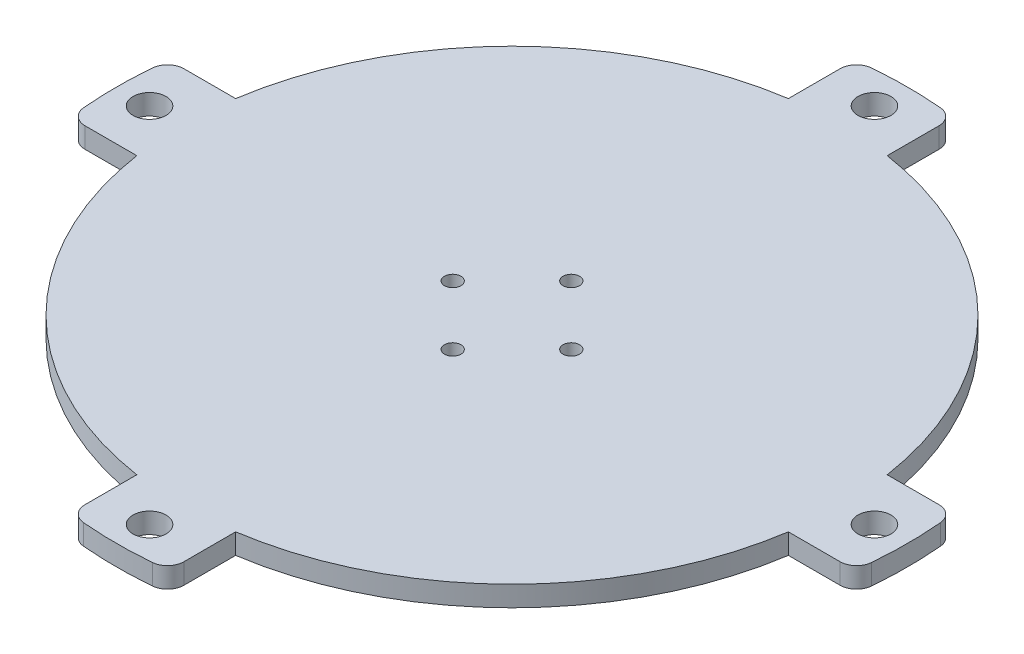
SolidWorks part; units mm, degrees
ref_plane "Front Plane" through (0, 0, 0) normal (0, 0, 1) x (1, 0, 0)
ref_plane "Top Plane" through (0, 0, 0) normal (0, 1, 0) x (1, 0, 0)
ref_plane "Right Plane" through (0, 0, 0) normal (1, 0, 0) x (0, 0, -1)
sketch "Sketch1" plane through (0, 0, 0) normal (0, 1, 0) x (1, 0, 0)
  line L97 (-15, -114.5644) -> (-15, -98.8686)
  line L98 (-114.5644, 15) -> (-98.8686, 15)
  line L99 (15, -98.8686) -> (15, -114.5644)
  line L100 (-98.8686, -15) -> (-114.5644, -15)
  line L101 (15, 114.5644) -> (15, 98.8686)
  line L102 (-15, 98.8686) -> (-15, 114.5644)
  line L103 (114.5644, -15) -> (98.8686, -15)
  line L104 (98.8686, 15) -> (114.5644, 15)
  arc A24 (-10.4348, -119.5455) -> (10.4348, -119.5455) centre (0, 0) ccw
  arc A25 (15, -98.8686) -> (98.8686, -15) centre (0, 0) ccw
  arc A26 (-119.5455, 10.4348) -> (-119.5455, -10.4348) centre (0, 0) ccw
  arc A27 (10.4348, 119.5455) -> (-10.4348, 119.5455) centre (0, 0) ccw
  arc A28 (119.5455, -10.4348) -> (119.5455, 10.4348) centre (0, 0) ccw
  arc A29 (-98.8686, -15) -> (-15, -98.8686) centre (0, 0) ccw
  arc A30 (-15, 98.8686) -> (-98.8686, 15) centre (0, 0) ccw
  arc A31 (98.8686, 15) -> (15, 98.8686) centre (0, 0) ccw
  circle A32 centre (0, -110) radius 5
  circle A33 centre (-110, 0) radius 5
  circle A34 centre (0, 110) radius 5
  circle A35 centre (110, 0) radius 5
  arc A36 (10.4348, 119.5455) -> (15, 114.5644) centre (10, 114.5644) cw
  arc A37 (-10.4348, 119.5455) -> (-15, 114.5644) centre (-10, 114.5644) ccw
  arc A38 (-119.5455, -10.4348) -> (-114.5644, -15) centre (-114.5644, -10) ccw
  arc A39 (-119.5455, 10.4348) -> (-114.5644, 15) centre (-114.5644, 10) cw
  arc A40 (119.5455, 10.4348) -> (114.5644, 15) centre (114.5644, 10) ccw
  arc A41 (119.5455, -10.4348) -> (114.5644, -15) centre (114.5644, -10) cw
  arc A42 (-15, -114.5644) -> (-10.4348, -119.5455) centre (-10, -114.5644) ccw
  arc A43 (15, -114.5644) -> (10.4348, -119.5455) centre (10, -114.5644) cw
  point P7 (0, -120)
  point P20 (0, 0)
  point P30 (0, 0)
  dimension "D1" = 240
  dimension "D5" = 4
  dimension "D7" = 10
  dimension "D8" = 4
  dimension "D9" = 5
  dimension "D2" = 200
  dimension "D4" = 15
  dimension "D6" = 10
  dimension "D3" = 30
extrude "Boss-Extrude1" add sketch "Sketch1" against normal blind 6.2
sketch "Sketch2" plane through (0, -6.2, 0) normal (0, -1, 0) x (1, 0, 0)
  circle A0 centre (18, 0) radius 2.5 construction
  circle A1 centre (0, -18) radius 2.5 construction
  circle A2 centre (-18, 0) radius 2.5 construction
  circle A3 centre (0, 18) radius 2.5 construction
  circle A4 centre (18, 0) radius 2.5
  circle A5 centre (0, -18) radius 2.5
  circle A6 centre (-18, 0) radius 2.5
  circle A7 centre (0, 18) radius 2.5
extrude "Cut-Extrude1" cut sketch "Sketch2" against normal up to next
